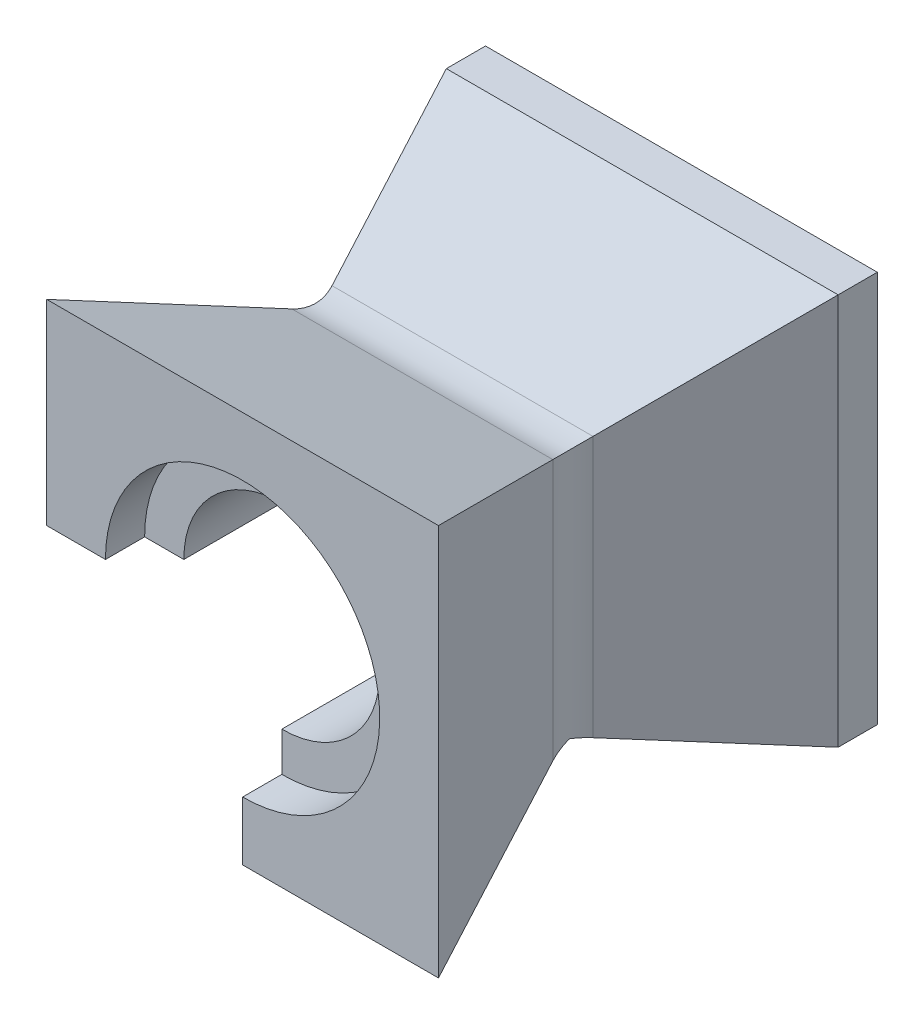
SolidWorks part; units mm, degrees
material "Acier inoxydable moulé"
ref_plane "Plan de face" through (0, 0, 0) normal (0, 0, 1) x (1, 0, 0)
ref_plane "Plan de dessus" through (0, 0, 0) normal (0, 1, 0) x (1, 0, 0)
ref_plane "Plan de droite" through (0, 0, 0) normal (1, 0, 0) x (0, 0, -1)
sketch "Esquisse2" plane through (0, 0, 0) normal (0, 0, 1) x (1, 0, 0)
  line L1 (-73.4104, 39.1618) -> (26.5896, 39.1618)
  line L2 (-73.4104, 39.1618) -> (-73.4104, -60.8382)
  line L3 (-73.4104, -60.8382) -> (26.5896, -60.8382)
  line L4 (26.5896, 39.1618) -> (26.5896, -60.8382)
  dimension "D1" = 100
  dimension "D2" = 100
extrude "Boss.-Extru.1" add sketch "Esquisse2" along normal blind 51 draft 20
mirror "Symétrie4" about plane through (0, 0, 51) normal (0, 0, 1) of "Boss.-Extru.1"
sketch "Esquisse3" plane through (0, 0, 102) normal (0, 0, 1) x (1, 0, 0)
  line L0 (26.5896, 39.1618) -> (-73.4104, -60.8382) construction
  line L1 (-73.4104, 39.1618) -> (26.5896, -60.8382) construction
  circle A0 centre (-23.4104, -10.8382) radius 25
  point P10 (-23.4104, -10.8382)
  point P11 (-23.4104, -10.8382)
  point P12 (-23.4104, -10.8382)
  point P13 (0, 0)
  dimension "D1" = 50
extrude "Enlèv. mat.-Extru.1" cut sketch "Esquisse3" against normal through all both and the other way through all
sketch "Esquisse5" plane through (0, 0, 102) normal (0, 0, 1) x (1, 0, 0)
  circle A0 centre (-23.4104, -10.8382) radius 35
  dimension "D1" = 70
extrude "Enlèv. mat.-Extru.2" cut sketch "Esquisse5" against normal blind 10 and the other way through all
sketch "Esquisse6" plane through (0, 0, 0) normal (0, 0, -1) x (-1, 0, 0)
  circle A1 centre (23.4104, -10.8382) radius 35
  circle A2 centre (23.4104, -10.8382) radius 35
  dimension "D1" = 0
extrude "Enlèv. mat.-Extru.3" cut sketch "Esquisse6" against normal blind 10
sketch "Esquisse7" plane through (0, 0, 0) normal (0, 0, -1) x (-1, 0, 0)
  line L0 (23.4104, -10.8382) -> (73.4104, -10.8382)
  line L1 (73.4104, 39.1618) -> (73.4104, -60.8382) construction
  line L2 (23.4104, -10.8382) -> (23.4104, -60.8382)
  line L3 (73.4104, -60.8382) -> (-26.5896, -60.8382) construction
  line L4 (23.4104, -60.8382) -> (73.4104, -60.8382)
  line L5 (73.4104, -60.8382) -> (73.4104, -10.8382)
extrude "Enlèv. mat.-Extru.4" cut sketch "Esquisse7" against normal through all
fillet "Congé1" radius 15 3 edges at (-54.8479, 4.8806, 51) (-23.4104, 20.5994, 51) (8.0271, -10.8382, 51)
sketch "Esquisse8" plane through (0, 0, 0) normal (0, 0, -1) x (-1, 0, 0)
  line L0 (23.4104, -10.8382) -> (-11.9449, 24.5172) construction
  line L1 (-26.5896, 39.1618) -> (-26.5896, -60.8382)
  line L2 (-11.9449, -46.1935) -> (58.7657, 24.5172) construction
  line L3 (-17.2482, 29.8205) -> (-6.6416, 19.2139) construction
  line L4 (-15.1269, 31.9418) -> (-4.5203, 21.3352)
  line L5 (-19.3696, 27.6992) -> (-8.763, 17.0926)
  line L6 (-4.5203, 17.0926) -> (-26.5896, 39.1618) construction
  line L7 (-17.2482, -51.4968) -> (-6.6416, -40.8902) construction
  line L12 (-19.3696, -49.3755) -> (-8.763, -38.7689)
  line L13 (-15.1269, -53.6181) -> (-4.5203, -43.0115)
  line L14 (53.4624, 19.2139) -> (64.069, 29.8205) construction
  line L15 (51.3411, 21.3352) -> (61.9477, 31.9418)
  line L16 (55.5838, 17.0926) -> (66.1904, 27.6992)
  line L17 (73.4104, -10.8382) -> (58.4104, -10.8382) construction
  line L18 (73.4104, 39.1618) -> (73.4104, -10.8382) construction
  line L19 (-26.5896, 39.1618) -> (73.4104, 39.1618) construction
  line L20 (-23.5896, 36.1618) -> (-23.5896, -57.8382)
  line L21 (23.4104, -60.8382) -> (-26.5896, -60.8382) construction
  line L22 (23.4104, -45.8382) -> (23.4104, -60.8382) construction
  line L23 (23.4104, -57.8382) -> (23.4104, -60.8382)
  line L24 (23.4104, -60.8382) -> (-26.5896, -60.8382)
  line L25 (-26.5896, 39.1618) -> (73.4104, 39.1618)
  line L26 (73.4104, 39.1618) -> (73.4104, -10.8382)
  line L27 (73.4104, -10.8382) -> (70.4104, -10.8382)
  line L29 (-26.5896, 36.1618) -> (73.4104, 36.1618)
  line L30 (-23.5896, 36.1618) -> (70.4104, 36.1618)
  line L32 (70.4104, 39.1618) -> (70.4104, -10.8382)
  line L33 (70.4104, 36.1618) -> (70.4104, -10.8382)
  line L35 (23.4104, -57.8382) -> (-26.5896, -57.8382)
  line L36 (23.4104, -57.8382) -> (-23.5896, -57.8382)
  circle A0 centre (23.4104, -10.8382) radius 50 construction
  arc A1 (-15.1269, 31.9418) -> (-19.3696, 27.6992) centre (-17.2482, 29.8205) ccw
  arc A2 (-8.763, 17.0926) -> (-4.5203, 21.3352) centre (-6.6416, 19.2139) ccw
  arc A7 (-19.3696, -49.3755) -> (-15.1269, -53.6181) centre (-17.2482, -51.4968) ccw
  arc A8 (-4.5203, -43.0115) -> (-8.763, -38.7689) centre (-6.6416, -40.8902) ccw
  arc A9 (51.3411, 21.3352) -> (55.5838, 17.0926) centre (53.4624, 19.2139) ccw
  arc A10 (66.1904, 27.6992) -> (61.9477, 31.9418) centre (64.069, 29.8205) ccw
  point P11 (-11.9449, 24.5172)
  point P18 (-11.9449, -46.1935)
  point P28 (58.7657, 24.5172)
  point P40 (-23.5896, 39.1618)
  point P41 (-23.5896, -60.8382)
  dimension "D1" = 15
  dimension "D2" = 3
  dimension "D3" = 3
  dimension "D4" = 15
  dimension "D6" = 3
  dimension "D7" = 3
  dimension "D8" = 3
extrude "Enlèv. mat.-Extru.8" cut sketch "Esquisse8" against normal blind 10 contours L5 A2 L4 A1 | L13 A8 L12 A7 | L15 A10 L16 A9
sketch "Esquisse9" plane through (0, 0, 0) normal (0, 0, -1) x (-1, 0, 0)
  line L2 (-4.5203, 21.3352) -> (-15.1269, 31.9418)
  line L3 (-19.3696, 27.6992) -> (-8.763, 17.0926)
  line L4 (-4.5203, 21.3352) -> (-15.1269, 31.9418)
  line L5 (-19.3696, 27.6992) -> (-8.763, 17.0926)
  line L6 (-8.763, -38.7689) -> (-19.3696, -49.3755)
  line L7 (-15.1269, -53.6181) -> (-4.5203, -43.0115)
  line L8 (-8.763, -38.7689) -> (-19.3696, -49.3755)
  line L9 (-15.1269, -53.6181) -> (-4.5203, -43.0115)
  line L10 (61.9477, 31.9418) -> (51.3411, 21.3352)
  line L11 (55.5838, 17.0926) -> (66.1904, 27.6992)
  line L12 (61.9477, 31.9418) -> (51.3411, 21.3352)
  line L13 (55.5838, 17.0926) -> (66.1904, 27.6992)
  line L22 (-26.5896, -60.8382) -> (23.4104, -60.8382)
  line L23 (-26.5896, 39.1618) -> (-26.5896, -60.8382)
  line L24 (73.4104, 39.1618) -> (-26.5896, 39.1618)
  line L25 (73.4104, -10.8382) -> (73.4104, 39.1618)
  line L26 (70.4104, -10.8382) -> (73.4104, -10.8382)
  line L27 (70.4104, 36.1618) -> (70.4104, -10.8382)
  line L28 (-23.5896, 36.1618) -> (70.4104, 36.1618)
  line L29 (-23.5896, -57.8382) -> (-23.5896, 36.1618)
  line L30 (23.4104, -57.8382) -> (-23.5896, -57.8382)
  line L31 (23.4104, -60.8382) -> (23.4104, -57.8382)
  line L32 (-26.5896, -60.8382) -> (23.4104, -60.8382)
  line L33 (-26.5896, 39.1618) -> (-26.5896, -60.8382)
  line L34 (73.4104, 39.1618) -> (-26.5896, 39.1618)
  line L35 (73.4104, -10.8382) -> (73.4104, 39.1618)
  line L36 (70.4104, -10.8382) -> (73.4104, -10.8382)
  line L37 (70.4104, 36.1618) -> (70.4104, -10.8382)
  line L38 (-23.5896, 36.1618) -> (70.4104, 36.1618)
  line L39 (-23.5896, -57.8382) -> (-23.5896, 36.1618)
  line L40 (23.4104, -57.8382) -> (-23.5896, -57.8382)
  line L41 (23.4104, -60.8382) -> (23.4104, -57.8382)
  arc A2 (-8.763, 17.0926) -> (-4.5203, 21.3352) centre (-6.6416, 19.2139) ccw
  arc A3 (-15.1269, 31.9418) -> (-19.3696, 27.6992) centre (-17.2482, 29.8205) ccw
  arc A4 (-8.763, 17.0926) -> (-4.5203, 21.3352) centre (-6.6416, 19.2139) ccw
  arc A5 (-15.1269, 31.9418) -> (-19.3696, 27.6992) centre (-17.2482, 29.8205) ccw
  arc A6 (-4.5203, -43.0115) -> (-8.763, -38.7689) centre (-6.6416, -40.8902) ccw
  arc A7 (-19.3696, -49.3755) -> (-15.1269, -53.6181) centre (-17.2482, -51.4968) ccw
  arc A8 (-4.5203, -43.0115) -> (-8.763, -38.7689) centre (-6.6416, -40.8902) ccw
  arc A9 (-19.3696, -49.3755) -> (-15.1269, -53.6181) centre (-17.2482, -51.4968) ccw
  arc A10 (66.1904, 27.6992) -> (61.9477, 31.9418) centre (64.069, 29.8205) ccw
  arc A11 (51.3411, 21.3352) -> (55.5838, 17.0926) centre (53.4624, 19.2139) ccw
  arc A12 (66.1904, 27.6992) -> (61.9477, 31.9418) centre (64.069, 29.8205) ccw
  arc A13 (51.3411, 21.3352) -> (55.5838, 17.0926) centre (53.4624, 19.2139) ccw
  dimension "D1" = 0
  dimension "D2" = 0
  dimension "D3" = 0
  dimension "D4" = 0
extrude "Boss.-Extru.2" add sketch "Esquisse9" along normal blind 10 contours L32 L41 L40 L39 L38 L37 L36 L35 L34 L33
equation "\"A\"= 102"
equation "\"B\"= 100"
equation "\"C\"= 20"
equation "\"D1@Esquisse2\"=\"B\""
equation "\"D2@Esquisse2\"=\"B\""
equation "\"D3@Boss.-Extru.1\"=\"C\""
equation "\"D1@Boss.-Extru.1\"=\"A\"/2"
